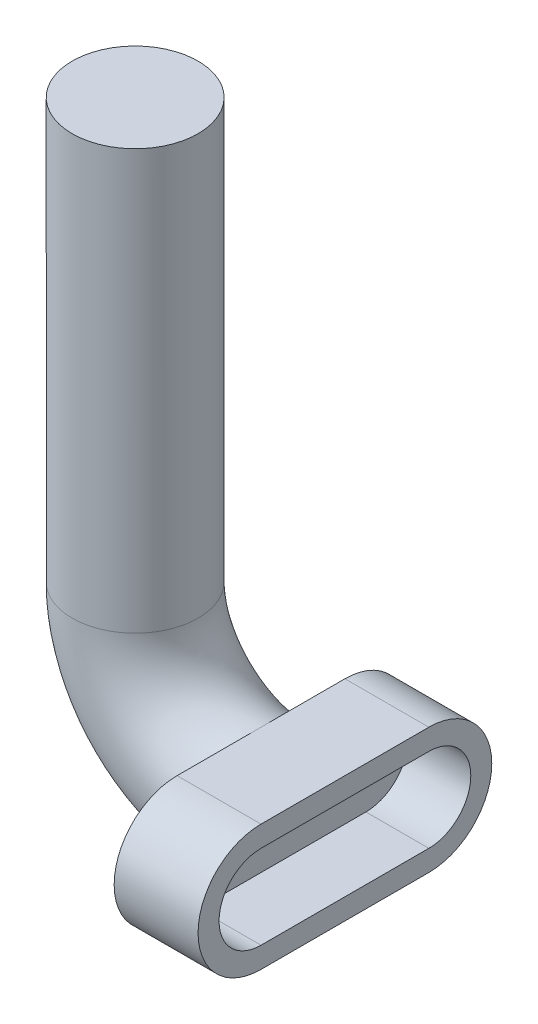
SolidWorks part; units mm, degrees
ref_plane "Front Plane" through (0, 0, 0) normal (0, 0, 1) x (1, 0, 0)
ref_plane "Top Plane" through (0, 0, 0) normal (0, 1, 0) x (1, 0, 0)
ref_plane "Right Plane" through (0, 0, 0) normal (1, 0, 0) x (0, 0, -1)
sketch "Sketch1" plane through (0, 0, 0) normal (1, 0, 0) x (0, 0, -1)
  line L0 (-25.4, 0) -> (25.4, 0) construction
  line L1 (-25.4, 19.05) -> (25.4, 19.05)
  line L2 (-25.4, -19.05) -> (25.4, -19.05)
  arc A0 (-25.4, 19.05) -> (-25.4, -19.05) centre (-25.4, 0) ccw
  arc A1 (25.4, -19.05) -> (25.4, 19.05) centre (25.4, 0) ccw
  point P3 (0, 0)
  point P8 (44.45, 0)
  point P9 (-44.45, 0)
  dimension "D1" = 19.05
  dimension "D2" = 50.8
extrude "Boss-Extrude1" add sketch "Sketch1" along normal blind 25.4
shell "Shell1" thickness 6.35
sketch "Sketch3" plane through (0, 0, 0) normal (0, 0, 1) x (1, 0, 0)
  line L0 (25.4, -19.05) -> (0, -19.05) construction
  line L1 (25.4, -19.05) -> (25.4, 19.05) construction
  line L2 (0, 19.05) -> (0, -19.05) construction
  line L3 (25.4, 19.05) -> (0, 19.05) construction
  line L4 (25.4, -19.05) -> (0, -19.05)
  line L5 (25.4, -19.05) -> (25.4, 19.05)
  line L6 (0, 19.05) -> (0, -19.05)
  line L7 (25.4, 19.05) -> (0, 19.05)
  line L8 (-38.1, 38.1) -> (-38.1, 165.1)
  line L9 (0, 0) -> (25.4, 0) construction
  line L11 (-19.05, 165.1) -> (-38.1, 165.1)
  line L12 (-38.1, 38.1) -> (-19.05, 38.1)
  arc A0 (0, 0) -> (-38.1, 38.1) centre (0, 38.1) cw
  point P9 (25.4, 0)
  point P11 (-0.3669, 0.0018)
  dimension "D1" = 127
  dimension "D2" = 38.1
sketch "Sketch7" plane through (0, 0, 0) normal (-1, 0, 0) x (0, 0, 1)
  circle A0 centre (0, 0) radius 19.05
  point P3 (0, 0)
  dimension "D1" = 38.1
sweep "Sweep1" add profiles "Sketch7" path "Sketch3"
